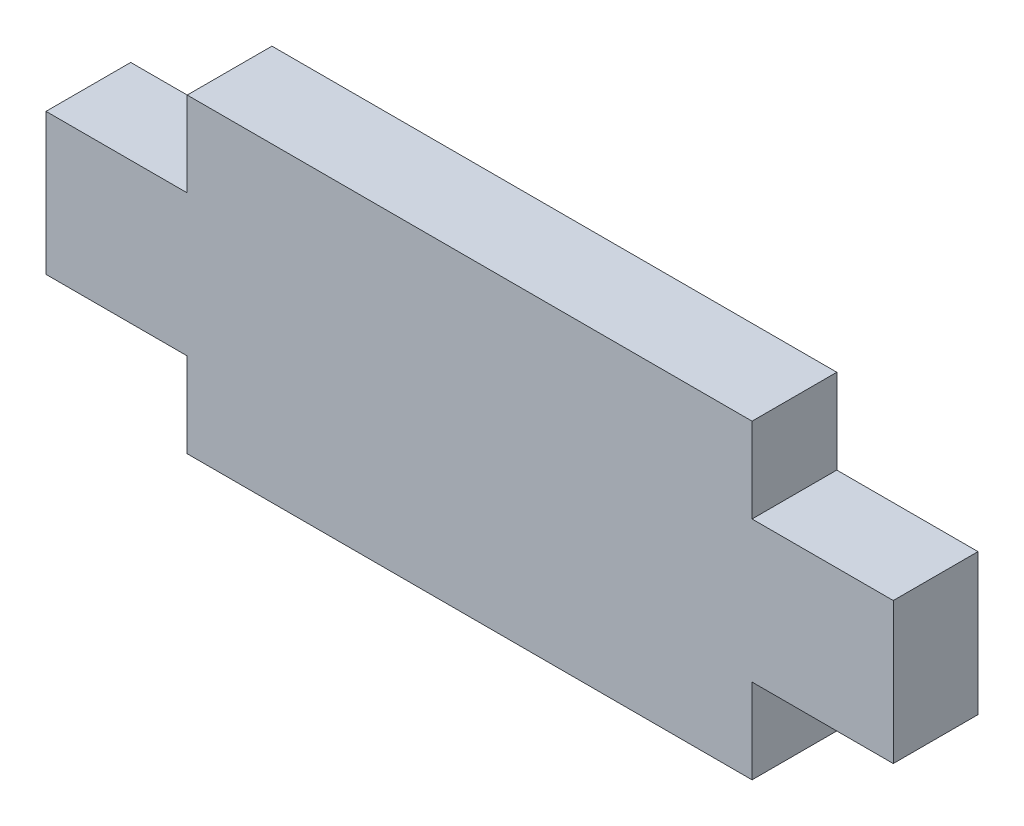
SolidWorks part; units mm, degrees
ref_plane "前视基准面" through (0, 0, 0) normal (0, 0, 1) x (1, 0, 0)
ref_plane "上视基准面" through (0, 0, 0) normal (0, 1, 0) x (1, 0, 0)
ref_plane "右视基准面" through (0, 0, 0) normal (1, 0, 0) x (0, 0, -1)
sketch "草图1" plane through (0, 0, 0) normal (0, 0, 1) x (1, 0, 0)
  line L0 (0, 2.5) -> (0, -2.5) construction
  line L1 (-15, 2.5) -> (15, 2.5)
  line L2 (-15, 2.5) -> (-15, -2.5)
  line L3 (-15, -2.5) -> (15, -2.5)
  line L4 (15, 2.5) -> (15, -2.5)
  line L5 (-15, 2.5) -> (15, -2.5) construction
  line L6 (-15, -2.5) -> (15, 2.5) construction
  line L7 (-15, 0) -> (15, 0) construction
  line L8 (-10, -2.5) -> (10, -2.5)
  line L9 (-10, 5.5) -> (10, 5.5)
  line L10 (-10, 5.5) -> (-10, 2.5)
  line L11 (-10, 2.5) -> (10, 2.5)
  line L12 (10, 5.5) -> (10, 2.5)
  line L13 (10, -5.5) -> (10, -2.5)
  line L14 (-10, -5.5) -> (10, -5.5)
  line L15 (-10, -5.5) -> (-10, -2.5)
  point P0 (0, 0)
  dimension "D1" = 3
  dimension "D2" = 5
  dimension "D3" = 20
  dimension "D4" = 30
extrude "凸台-拉伸1" add sketch "草图1" along normal blind 3 contours L12 L9 L10 L1 | L4 L1 L2 L3 | L15 L14 L13 L3
